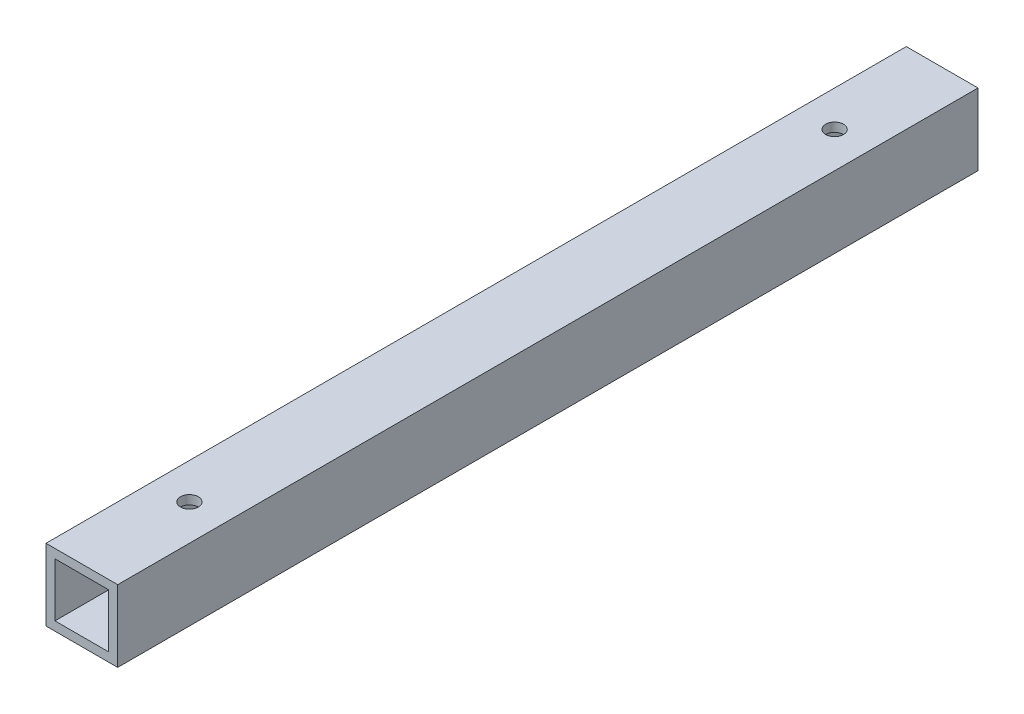
SolidWorks part; units mm, degrees
material "6061 Alloy"
ref_plane "Front Plane" through (0, 0, 0) normal (0, 0, 1) x (1, 0, 0)
ref_plane "Top Plane" through (0, 0, 0) normal (0, 1, 0) x (1, 0, 0)
ref_plane "Right Plane" through (0, 0, 0) normal (1, 0, 0) x (0, 0, -1)
sketch "Sketch1" plane through (0, 0, 0) normal (0, 0, 1) x (1, 0, 0)
  line L0 (12.7, 0) -> (9.525, 0) construction
  line L1 (-12.7, 0) -> (12.7, 0) construction
  line L2 (0, 12.7) -> (0, -12.7)
  point P7 (0, 0)
sketch "Sketch2" plane through (0, 0, 0) normal (1, 0, 0) x (0, 0, -1)
  line L0 (152.4, 0) -> (-152.4, 0)
  point P4 (0, 0)
  dimension "Length" = 304.8
sketch "Sketch3" plane through (0, 0, 0) normal (0, 0, 1) x (1, 0, 0)
  line L0 (-12.7, 0) -> (12.7, 0) construction
  line L5 (12.7, -12.7) -> (-12.7, -12.7)
  line L6 (12.7, -12.7) -> (12.7, 12.7)
  line L11 (12.7, 12.7) -> (-12.7, 12.7)
  line L12 (-12.7, -12.7) -> (-12.7, 12.7)
  line L14 (12.7, -12.7) -> (-12.7, 12.7) construction
  line L15 (12.7, 12.7) -> (-12.7, -12.7) construction
  line L16 (9.525, -9.525) -> (-9.525, -9.525)
  line L17 (9.525, -9.525) -> (9.525, 9.525)
  line L18 (9.525, 9.525) -> (-9.525, 9.525)
  line L19 (-9.525, -9.525) -> (-9.525, 9.525)
  line L20 (9.525, -9.525) -> (-9.525, 9.525) construction
  line L21 (9.525, 9.525) -> (-9.525, -9.525) construction
  point P0 (0, 0)
  point P5 (0, 0)
  point P13 (9.525, -12.7)
  dimension "D1" = 3.175
  dimension "D3" = 25.4
  dimension "D4" = 25.4
extrude "Boss-Extrude1" add sketch "Sketch3" along normal up to vertex (152.4 mm away) and the other way up to vertex (152.4 mm away) up to point (0, 0, 152.4) other way up to point (0, 0, -152.4)
sketch "Sketch5" plane through (0, 0, 0) normal (1, 0, 0) x (0, 0, -1)
  line L0 (-152.4, 0) -> (152.4, 0) construction
  line L3 (-152.4, -12.7) -> (-152.4, 12.7) construction
  line L4 (152.4, -12.7) -> (152.4, 12.7) construction
  point P6 (-123.825, 0)
  point P7 (-114.3, 0)
  point P8 (114.3, 0)
  point P10 (123.825, 0)
  dimension "D1" = 28.575
  dimension "D2" = 38.1
  dimension "D3" = 28.575
  dimension "D4" = 38.1
sketch "Sketch6" plane through (0, 12.7, 0) normal (0, -1, 0) x (0, 0, -1)
  line L1 (-152.4, 0) -> (152.4, 0) construction
  line L3 (-152.4, 12.7) -> (-152.4, -12.7) construction
  line L4 (152.4, 12.7) -> (152.4, -12.7) construction
  line L5 (0, 0) -> (0, -12.7) construction
  line L6 (-152.4, -12.7) -> (152.4, -12.7) construction
  circle A2 centre (-114.3, 0) radius 3.175
  circle A3 centre (114.3, 0) radius 3.175
  dimension "D1" = 6.35
  dimension "D2" = 38.1
extrude "Cut-Extrude1" cut sketch "Sketch6" along normal through all
equation "\"D1@Sketch3\"=\"Wall thickness@Sketch1\""
equation "\"D1@Sketch5\"=\"Width@Sketch1\"*1.125"
equation "\"D2@Sketch5\"=\"Width@Sketch1\"*1.5"
equation "\"D3@Sketch5\"=\"D1@Sketch5\""
equation "\"D4@Sketch5\"=\"D2@Sketch5\""
equation "\"D2@Sketch3\"=\"Wall Thickness@Sketch1\""
